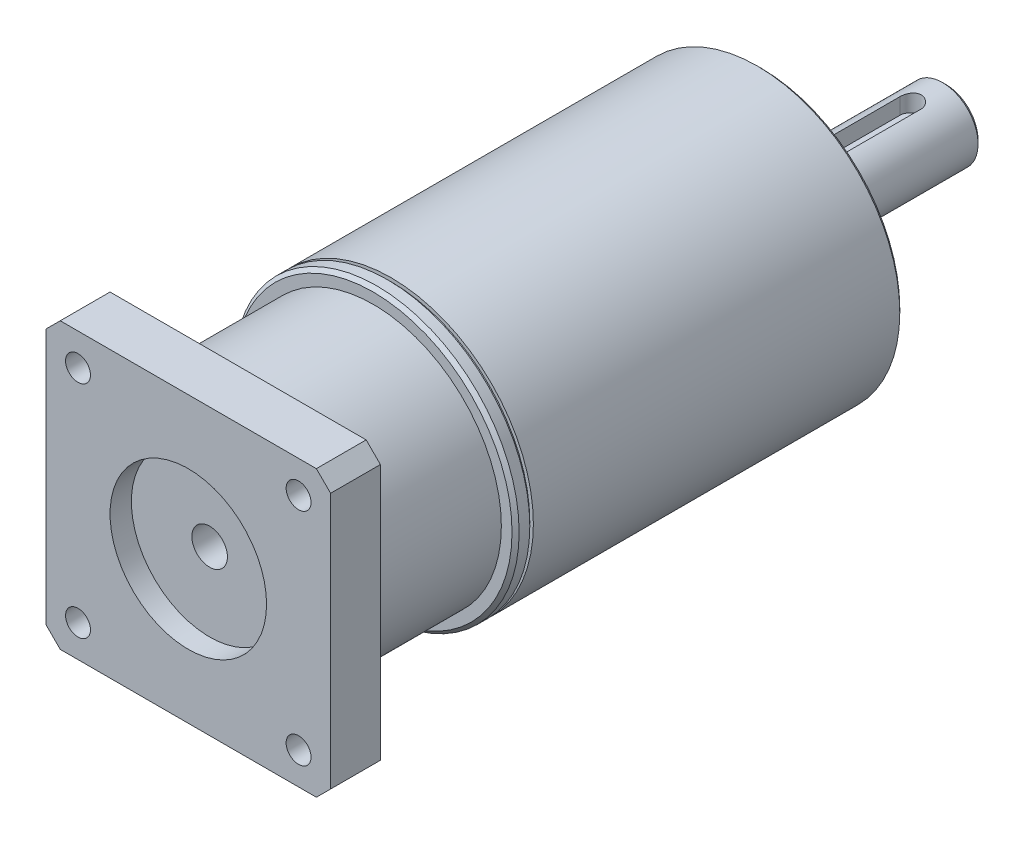
SolidWorks part; units mm, degrees
ref_plane "前视基准面" through (0, 0, 0) normal (0, 0, 1) x (1, 0, 0)
ref_plane "上视基准面" through (0, 0, 0) normal (0, 1, 0) x (1, 0, 0)
ref_plane "右视基准面" through (0, 0, 0) normal (1, 0, 0) x (0, 0, -1)
sketch "草图1" plane through (0, 0, 0) normal (0, 0, 1) x (1, 0, 0)
  line L1 (-20, -20) -> (20, -20)
  line L2 (-20, -20) -> (-20, 20)
  line L3 (-20, 20) -> (20, 20)
  line L4 (20, -20) -> (20, 20)
  line L5 (-20, -20) -> (20, 20) construction
  line L6 (-20, 20) -> (20, -20) construction
  point P0 (0, 0)
  dimension "D1" = 40
  dimension "D2" = 40
extrude "凸台-拉伸1" add sketch "草图1" along normal blind 7
sketch "草图2" plane through (0, 0, 7) normal (0, 0, 1) x (1, 0, 0)
  circle A0 centre (0, 0) radius 18
  dimension "D1" = 36
extrude "凸台-拉伸2" add sketch "草图2" against normal blind 26
sketch "草图3" plane through (0, 0, -19) normal (0, 0, -1) x (-1, 0, 0)
  circle A0 centre (0, 0) radius 20
extrude "凸台-拉伸3" add sketch "草图3" along normal blind 54.5
sketch "草图4" plane through (0, 0, 0) normal (0, 1, 0) x (1, 0, 0)
  line L0 (0, 0) -> (0, 58.7245) construction
  line L1 (-20, 19) -> (20, 19) construction
  line L2 (19.5, 21.5) -> (21.8061, 21.5)
  line L3 (19.5, 21.5) -> (19.5, 21)
  line L4 (19.5, 21) -> (21.8061, 21)
  line L5 (21.8061, 21.5) -> (21.8061, 21)
  line L6 (19.5, 21.5) -> (21.8061, 21) construction
  line L7 (19.5, 21) -> (21.8061, 21.5) construction
  line L8 (20, 19) -> (20, 73.5) construction
  point P3 (20.6531, 21.25)
  dimension "D1" = 2.5
  dimension "D2" = 0.5
  dimension "D3" = 0.5
revolve "切除-旋转1" cut sketch "草图4" angle 360 about L0
sketch "草图5" plane through (0, 0, -73.5) normal (0, 0, -1) x (-1, 0, 0)
  circle A0 centre (0, 0) radius 13
  dimension "D1" = 26
extrude "凸台-拉伸4" add sketch "草图5" along normal blind 2
sketch "草图6" plane through (0, 0, -75.5) normal (0, 0, -1) x (-1, 0, 0)
  circle A0 centre (0, 0) radius 6
  dimension "D1" = 12
extrude "凸台-拉伸5" add sketch "草图6" along normal blind 1
sketch "草图7" plane through (0, 0, -76.5) normal (0, 0, -1) x (-1, 0, 0)
  circle A0 centre (0, 0) radius 5
  dimension "D1" = 10
extrude "凸台-拉伸6" add sketch "草图7" along normal blind 23
chamfer "倒角1" distance 2 angle 45 4 edges at (-20, 20, 3.5) (-20, -20, 3.5) (20, 20, 3.5) (20, -20, 3.5)
chamfer "倒角2" distance 0.5 angle 45 4 edges at (-5, 0, -99.5) (-6, 0, -76.5) (-20, 0, -73.5) (-20, 0, -19)
sketch "草图8" plane through (0, 0, 7) normal (0, 0, 1) x (1, 0, 0)
  circle A0 centre (-15.5, 15.5) radius 1.75
  dimension "D1" = 3.5
  dimension "D2" = 15.5
  dimension "D3" = 15.5
extrude "切除-拉伸1" cut sketch "草图8" against normal blind 20
pattern_circular "阵列(圆周)1" count 4 every 90 about axis through (0, 0, 0) along (0, 0, 1) of "切除-拉伸1"
sketch "草图9" plane through (0, 0, 7) normal (0, 0, 1) x (1, 0, 0)
  circle A0 centre (0, 0) radius 11
  dimension "D1" = 22
extrude "切除-拉伸2" cut sketch "草图9" against normal blind 3
sketch "草图10" plane through (0, 0, 4) normal (0, 0, 1) x (1, 0, 0)
  circle A0 centre (0, 0) radius 2.5
  dimension "D1" = 5
extrude "切除-拉伸3" cut sketch "草图10" against normal blind 23
hole_wizard "M4 螺纹孔1" positions "草图12" profile "草图11" tap size "M4" standard "GB"
sketch "草图12" plane through (0, 0, -73.5) normal (0, 0, -1) x (-1, 0, 0)
  line L0 (15.5, 15.5) -> (0, 0) construction
  point P0 (12.0208, 12.0208)
  dimension "D1" = 17
sketch "草图11" plane through (-12.0208, 12.0208, -73.5) normal (1, 0, 0) x (0, 1, 0)
  line L0 (0, 0) -> (0, 10.9914)
  line L1 (0, 10.9914) -> (1.65, 10)
  line L2 (1.65, 10) -> (1.65, 0)
  line L5 (1.65, 0) -> (0, 0)
  line L10 (0, 10.9914) -> (-1.65, 10) construction
  line L11 (0, -6.35) -> (0, 107.95) construction
  dimension "螺纹孔钻头直径" = 3.3
  dimension "螺纹孔钻头深度" = 10
  dimension "导头角度" = 118
cosmetic thread "孔螺蚊线1" parameters "D1"=10, "D2"=4
pattern_circular "阵列(圆周)2" count 4 every 90 about axis through (0, 0, 0) along (0, 0, 1) of "M4 螺纹孔1"
ref_plane "基准面1" through (0, 5, 0) normal (0, 1, 0) x (1, 0, 0)
sketch "草图13" plane through (0, 5, 0) normal (0, 1, 0) x (1, 0, 0)
  line L0 (0, 94.5) -> (0, 81.5) construction
  line L1 (1.5, 94.5) -> (1.5, 81.5)
  line L2 (-1.5, 94.5) -> (-1.5, 81.5)
  line L3 (4.5, 99.5) -> (-4.5, 99.5) construction
  arc A0 (1.5, 94.5) -> (-1.5, 94.5) centre (0, 94.5) ccw
  arc A1 (-1.5, 81.5) -> (1.5, 81.5) centre (0, 81.5) ccw
  point P2 (0, 88)
  dimension "D1" = 1.5
  dimension "D2" = 13
  dimension "D3" = 5
extrude "切除-拉伸4" cut sketch "草图13" against normal blind 2.5
